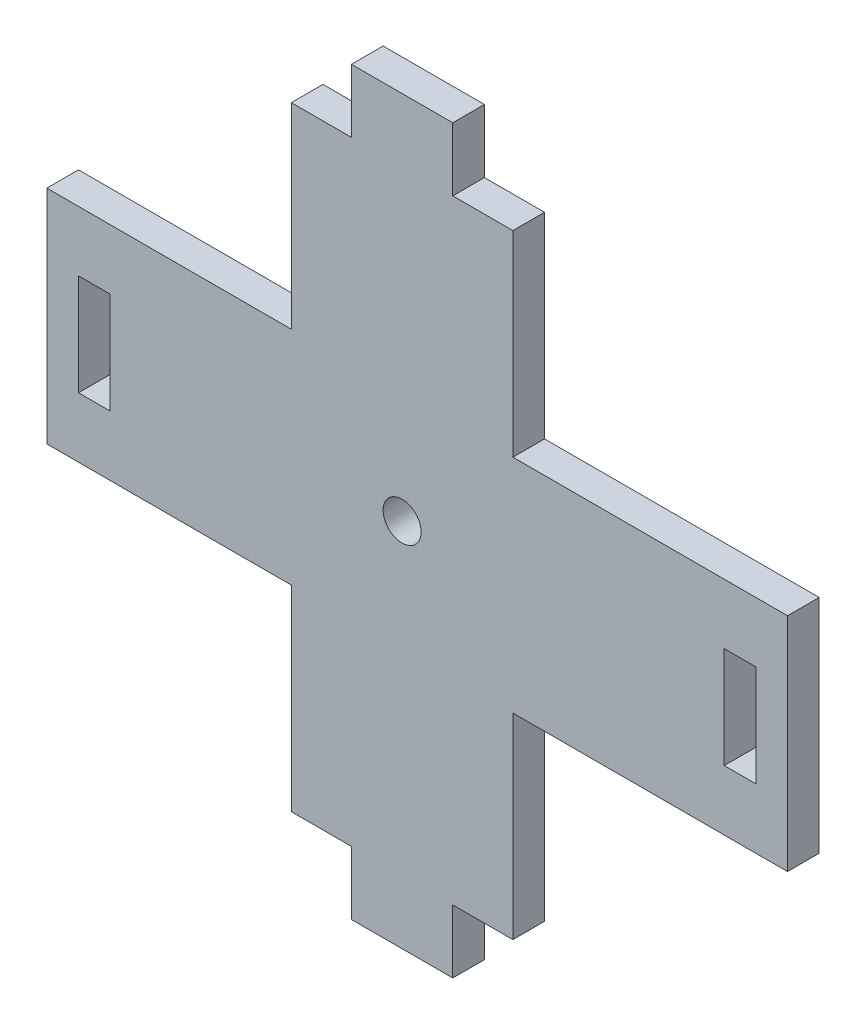
SolidWorks part; units mm, degrees
ref_plane "Front Plane" through (0, 0, 0) normal (0, 0, 1) x (1, 0, 0)
ref_plane "Top Plane" through (0, 0, 0) normal (0, 1, 0) x (1, 0, 0)
ref_plane "Right Plane" through (0, 0, 0) normal (1, 0, 0) x (0, 0, -1)
sketch "Sketch1" plane through (0, 0, 0) normal (0, 0, 1) x (1, 0, 0)
  line L0 (0, 17.5) -> (117, 17.5) construction
  line L1 (0, 0) -> (38.6195, 0)
  line L2 (0, 0) -> (0, 35)
  line L3 (0, 35) -> (38.6195, 35)
  line L4 (117, 0) -> (117, 35)
  line L5 (38.6195, 66) -> (48.1195, 66)
  line L6 (38.6195, 66) -> (38.6195, 35)
  line L7 (38.6195, -31) -> (48.1195, -31)
  line L8 (73.6195, 66) -> (73.6195, 35)
  line L9 (56.1195, 17.5) -> (56.1195, 0) construction
  line L10 (41, 17.5) -> (76, 17.5) construction
  line L11 (56.1195, 66) -> (56.1195, 35) construction
  line L12 (73.6195, 35) -> (117, 35)
  line L13 (56.1195, 17.5) -> (56.1195, 0) construction
  line L14 (73.6195, 0) -> (117, 0)
  line L15 (73.6195, 0) -> (73.6195, -31)
  line L16 (38.6195, 0) -> (38.6195, -31)
  line L17 (48.1195, 71) -> (64.1195, 71) construction
  line L18 (48.1195, 76) -> (64.1195, 76)
  line L19 (48.1195, 76) -> (48.1195, 66)
  line L21 (64.1195, 76) -> (64.1195, 66)
  line L23 (48.1195, -31) -> (48.1195, -41)
  line L24 (48.1195, -41) -> (64.1195, -41)
  line L25 (64.1195, -31) -> (64.1195, -41)
  line L26 (56.1195, 76) -> (56.1195, 71) construction
  line L27 (48.1195, -36) -> (64.1195, -36) construction
  line L28 (56.1195, -41) -> (56.1195, -36) construction
  line L29 (64.1195, -31) -> (73.6195, -31)
  line L30 (64.1195, 66) -> (73.6195, 66)
  dimension "D1" = 117
  dimension "D2" = 35
  dimension "D3" = 35
  dimension "D4" = 97
  dimension "D5" = 16
  dimension "D6" = 10
  dimension "D7" = 10
  dimension "D8" = 16
extrude "Boss-Extrude3" add sketch "Sketch1" along normal blind 5
sketch "Sketch2" plane through (0, 0, 5) normal (0, 0, 1) x (1, 0, 0)
  line L0 (0, 35) -> (0, 0) construction
  line L1 (5, 25.5) -> (10, 25.5)
  line L2 (5, 25.5) -> (5, 9.5)
  line L3 (5, 9.5) -> (10, 9.5)
  line L4 (10, 25.5) -> (10, 9.5)
  line L5 (107, 25.5) -> (112, 25.5)
  line L6 (107, 25.5) -> (107, 9.5)
  line L7 (107, 9.5) -> (112, 9.5)
  line L8 (112, 25.5) -> (112, 9.5)
  line L9 (0, 17.5) -> (117, 17.5) construction
  line L10 (117, 0) -> (117, 35) construction
  line L11 (5, 17.5) -> (10, 17.5) construction
  line L12 (107, 17.5) -> (112, 17.5) construction
  dimension "D1" = 5
  dimension "D2" = 5
  dimension "D3" = 16
  dimension "D4" = 5
  dimension "D5" = 16
  dimension "D6" = 5
extrude "Cut-Extrude1" cut sketch "Sketch2" against normal through all
sketch "Sketch3" plane through (0, 0, 5) normal (0, 0, 1) x (1, 0, 0)
  line L0 (0, 17.5) -> (117, 17.5) construction
  line L1 (0, 35) -> (0, 0) construction
  line L2 (117, 0) -> (117, 35) construction
  line L3 (56.1195, -41) -> (56.1195, 76) construction
  line L4 (48.1195, -41) -> (64.1195, -41) construction
  line L5 (64.1195, 76) -> (48.1195, 76) construction
  circle A0 centre (56.1195, 17.5) radius 3
  point P14 (0, 0)
  point P15 (0, 0)
  point P16 (0, 0)
  point P17 (0, 0)
  point P18 (0, 0)
  dimension "D1" = 6
extrude "Cut-Extrude2" cut sketch "Sketch3" against normal through all
